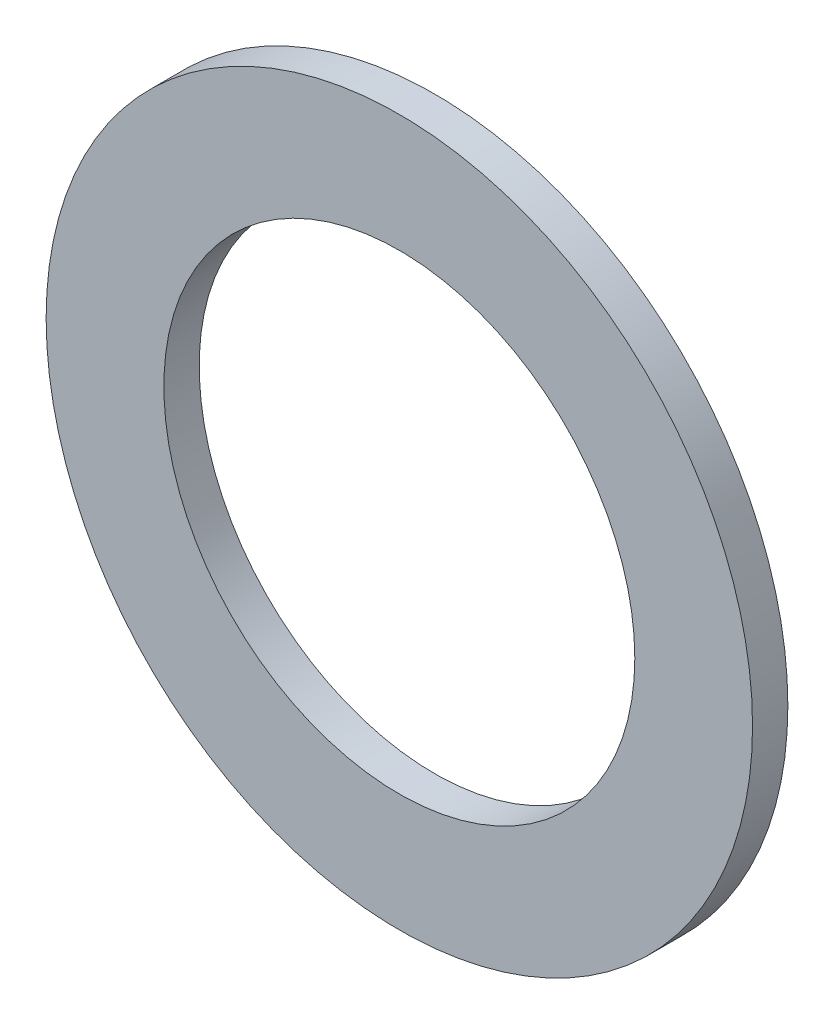
SolidWorks part; units mm, degrees
ref_plane "前视基准面" through (0, 0, 0) normal (0, 0, 1) x (1, 0, 0)
ref_plane "上视基准面" through (0, 0, 0) normal (0, 1, 0) x (1, 0, 0)
ref_plane "右视基准面" through (0, 0, 0) normal (1, 0, 0) x (0, 0, -1)
sketch "草图2" plane through (0, 0, 0) normal (0, 0, 1) x (1, 0, 0)
  circle A0 centre (0, 0) radius 20
  circle A1 centre (0, 0) radius 30
  dimension "D1" = 60
  dimension "D2" = 40
extrude "凸台-拉伸1" add sketch "草图2" along normal blind 3
